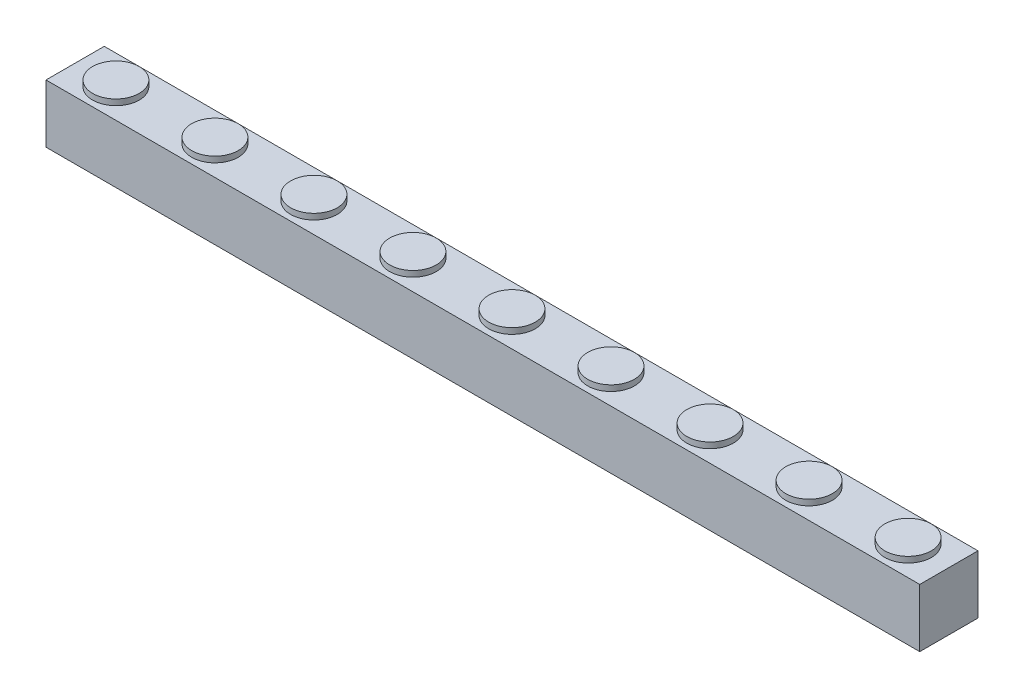
SolidWorks part; units mm, degrees
ref_plane "Front Plane" through (0, 0, 0) normal (0, 0, 1) x (1, 0, 0)
ref_plane "Top Plane" through (0, 0, 0) normal (0, 1, 0) x (1, 0, 0)
ref_plane "Right Plane" through (0, 0, 0) normal (1, 0, 0) x (0, 0, -1)
sketch "Sketch1" plane through (0, 0, 0) normal (0, 1, 0) x (1, 0, 0)
  line L1 (-75, -5) -> (75, -5)
  line L2 (-75, -5) -> (-75, 5)
  line L3 (-75, 5) -> (75, 5)
  line L4 (75, -5) -> (75, 5)
  line L5 (-75, -5) -> (75, 5) construction
  line L6 (-75, 5) -> (75, -5) construction
  point P0 (0, 0)
extrude "Boss-Extrude1" add sketch "Sketch1" along normal blind 10
sketch "Sketch2" plane through (0, 10, 0) normal (0, 1, 0) x (1, 0, 0)
  circle A0 centre (0, 0) radius 4
  circle A1 centre (17, 0) radius 4
  circle A2 centre (34, 0) radius 4
  circle A3 centre (51, 0) radius 4
  circle A4 centre (68, 0) radius 4
  circle A5 centre (-17, 0) radius 4
  circle A6 centre (-34, 0) radius 4
  circle A7 centre (-51, 0) radius 4
  circle A8 centre (-68, 0) radius 4
  dimension "D1" = 5
  dimension "D2" = 5
extrude "Boss-Extrude2" add sketch "Sketch2" along normal blind 1
